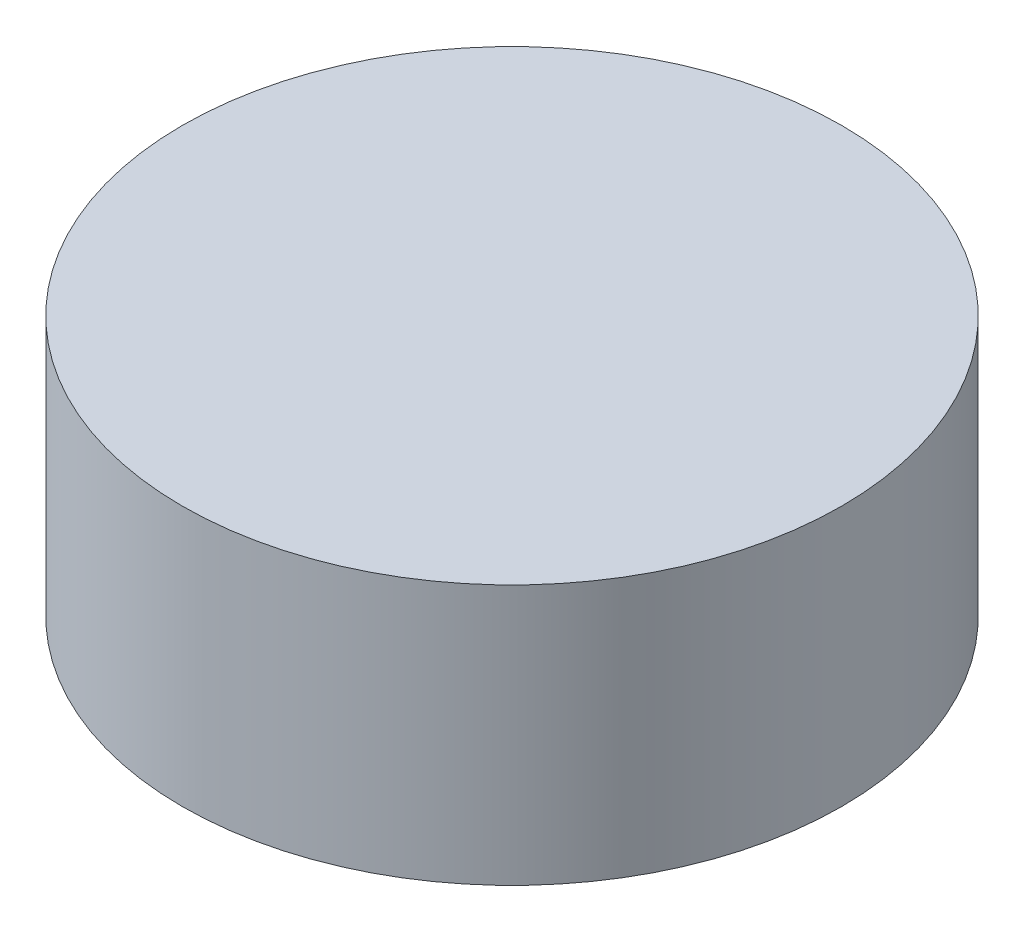
SolidWorks part; units mm, degrees
material "Cast Alloy Steel"
ref_plane "Front Plane" through (0, 0, 0) normal (0, 0, 1) x (1, 0, 0)
ref_plane "Top Plane" through (0, 0, 0) normal (0, 1, 0) x (1, 0, 0)
ref_plane "Right Plane" through (0, 0, 0) normal (1, 0, 0) x (0, 0, -1)
sketch "Sketch1" plane through (0, 0, 0) normal (0, 1, 0) x (1, 0, 0)
  circle A0 centre (0, 0) radius 38.0107
extrude "Boss-Extrude1" add sketch "Sketch1" along normal blind 30
